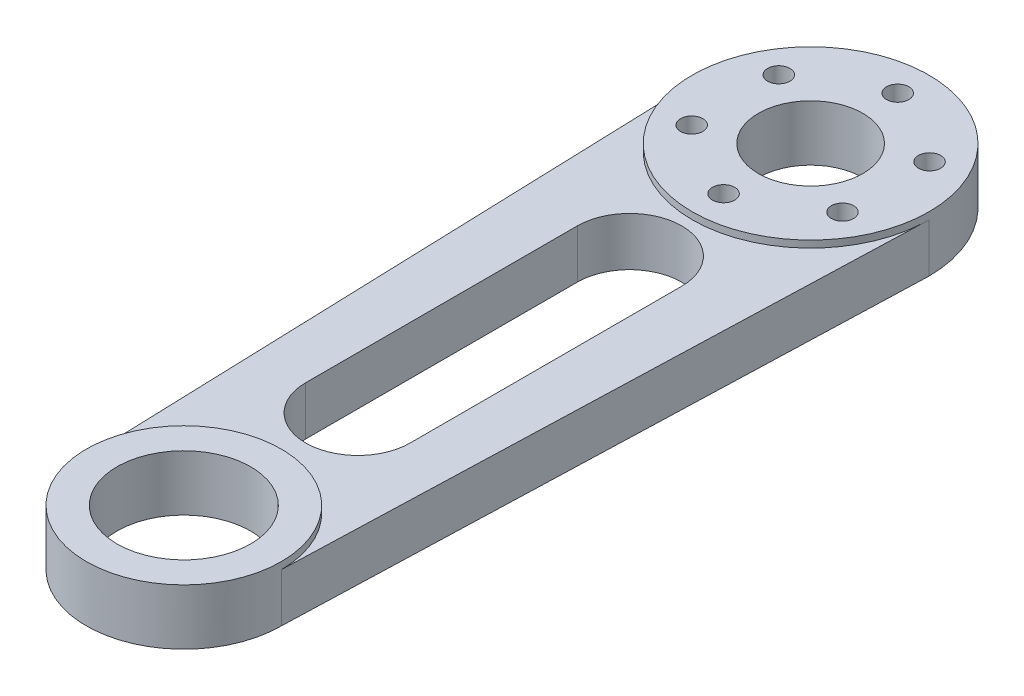
SolidWorks part; units mm, degrees
material "6061 合金"
ref_plane "前视基准面" through (0, 0, 0) normal (0, 0, 1) x (1, 0, 0)
ref_plane "上视基准面" through (0, 0, 0) normal (0, 1, 0) x (1, 0, 0)
ref_plane "右视基准面" through (0, 0, 0) normal (1, 0, 0) x (0, 0, -1)
sketch "草图2" plane through (0, 0, 0) normal (0, 1, 0) x (1, 0, 0)
  line L0 (-43.3098, 0) -> (41.7057, 0) construction
  line L1 (0, 37.455) -> (0, -121.0546) construction
  line L2 (0, 0) -> (0, -90) construction
  line L3 (-14, -90) -> (-17, 0)
  line L4 (14, -90) -> (17, 0)
  circle A0 centre (0, 0) radius 12.5 construction
  circle A1 centre (0, 0) radius 17
  circle A2 centre (0, 12.5) radius 1.6
  circle A3 centre (10.8253, 6.25) radius 1.6
  circle A4 centre (10.8253, -6.25) radius 1.6
  circle A5 centre (0, -12.5) radius 1.6
  circle A6 centre (-10.8253, -6.25) radius 1.6
  circle A7 centre (-10.8253, 6.25) radius 1.6
  circle A8 centre (0, 0) radius 7.5
  circle A9 centre (0, -90) radius 9.6
  circle A10 centre (0, -90) radius 14
  point P22 (0, 0)
  dimension "D1" = 90
  dimension "D2" = 6
extrude "凸台-拉伸1" add sketch "草图2" along normal blind 7 contours A10 L4 A1 L3 | A10 A9 | L4 A1 L3 A8 A7 A6 A5 A4 A3 A2
sketch "草图4" plane through (0, 7, 0) normal (0, 1, 0) x (1, 0, 0)
  line L0 (0, -26) -> (0, -65) construction
  line L1 (7.5, -26) -> (7.5, -65)
  line L2 (-7.5, -26) -> (-7.5, -65)
  line L3 (0, 20.2892) -> (0, -114.0539) construction
  arc A0 (7.5, -26) -> (-7.5, -26) centre (0, -26) ccw
  arc A1 (-7.5, -65) -> (7.5, -65) centre (0, -65) ccw
  circle A3 centre (0, -90) radius 9.6 construction
  point P3 (0, -45.5)
  dimension "D1" = 26
  dimension "D2" = 25
  dimension "D3" = 15
extrude "切除-拉伸1" cut sketch "草图4" against normal blind 8
sketch "草图5" plane through (0, 7, 0) normal (0, 1, 0) x (1, 0, 0)
  circle A0 centre (0, -90) radius 14
  circle A1 centre (0, -90) radius 9.6
extrude "凸台-拉伸3" add sketch "草图5" along normal blind 1
sketch "草图6" plane through (0, 7, 0) normal (0, 1, 0) x (1, 0, 0)
  circle A0 centre (0, 0) radius 7.5
  circle A1 centre (0, 0) radius 17
  circle A2 centre (0, 12.5) radius 1.6
  circle A3 centre (10.8253, 6.25) radius 1.6
  circle A4 centre (10.8253, -6.25) radius 1.6
  circle A5 centre (0, -12.5) radius 1.6
  circle A6 centre (-10.8253, -6.25) radius 1.6
  circle A7 centre (-10.8253, 6.25) radius 1.6
  point P19 (0, 0)
  dimension "D1" = 6
extrude "凸台-拉伸4" add sketch "草图6" along normal blind 1
